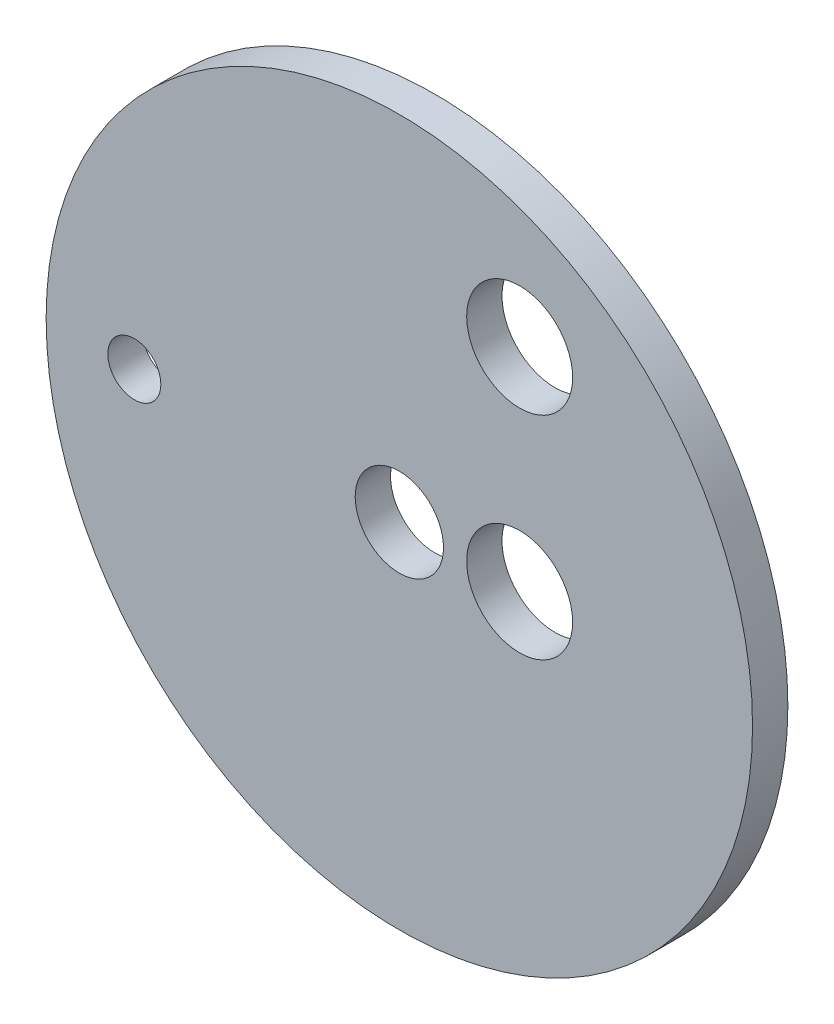
SolidWorks part; units mm, degrees
ref_plane "Front Plane" through (0, 0, 0) normal (0, 0, 1) x (1, 0, 0)
ref_plane "Top Plane" through (0, 0, 0) normal (0, 1, 0) x (1, 0, 0)
ref_plane "Right Plane" through (0, 0, 0) normal (1, 0, 0) x (0, 0, -1)
sketch "Sketch1" plane through (0, 0, 0) normal (0, 0, 1) x (1, 0, 0)
  circle A0 centre (0, 0) radius 100
  dimension "D1" = 200
extrude "Boss-Extrude1" add sketch "Sketch1" along normal blind 10
sketch "Sketch2" plane through (0, 0, 10) normal (0, 0, 1) x (1, 0, 0)
  circle A0 centre (-75.0278, 0) radius 7.5
  circle A1 centre (75.0278, 0) radius 7.5
  dimension "D1" = 15
sketch "Sketch3" plane through (0, 0, 0) normal (0, 0, -1) x (-1, 0, 0)
  circle A0 centre (0, 0) radius 12.5
  dimension "D1" = 25
extrude "Cut-Extrude2" cut sketch "Sketch3" against normal blind 20
extrude "Cut-Extrude3" cut sketch "Sketch2" against normal blind 10 contours A0
sketch "Sketch5" plane through (0, 0, 10) normal (0, 0, 1) x (1, 0, 0)
  line L0 (49.0614, 0) -> (79.0614, 0) construction
  circle A0 centre (34.0614, 0) radius 15
  circle A1 centre (79.0614, 0) radius 15
  dimension "D1" = 30
  dimension "D3" = 30
  dimension "D2" = 30
extrude "Cut-Extrude5" cut sketch "Sketch5" against normal blind 10
sketch "Sketch6" plane through (0, 0, 0) normal (0, 0, -1) x (-1, 0, 0)
  circle A0 centre (-79.0614, 0) radius 15
extrude "Boss-Extrude2" add sketch "Sketch6" against normal blind 10
sketch "Sketch7" plane through (0, 0, 0) normal (0, 0, -1) x (-1, 0, 0)
  line L0 (-34.0614, 60) -> (-34.0614, 0) construction
  circle A0 centre (-34.0614, 60) radius 15
  circle A1 centre (-34.0614, 0) radius 15 construction
  dimension "D1" = 60
extrude "Cut-Extrude6" cut sketch "Sketch7" against normal blind 30
